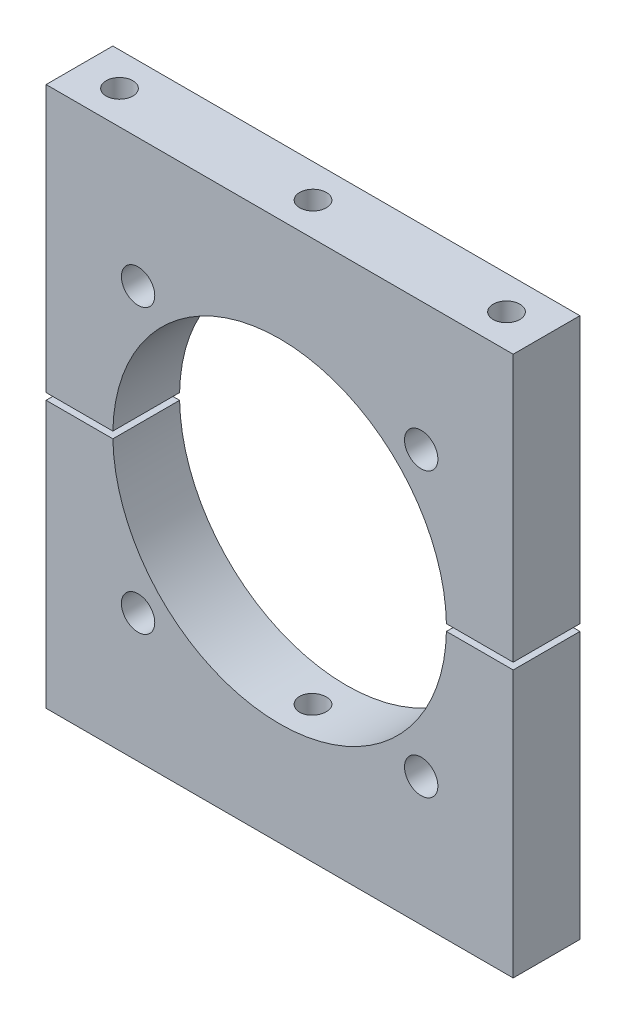
SolidWorks part; units mm, degrees
material "6061 Alloy"
ref_plane "Front Plane" through (0, 0, 0) normal (0, 0, 1) x (1, 0, 0)
ref_plane "Top Plane" through (0, 0, 0) normal (0, 1, 0) x (1, 0, 0)
ref_plane "Right Plane" through (0, 0, 0) normal (1, 0, 0) x (0, 0, -1)
sketch "Sketch1" plane through (0, 0, 0) normal (0, 0, 1) x (1, 0, 0)
  line L1 (0, 0) -> (70, 0)
  line L2 (0, 0) -> (0, 80.96)
  line L3 (0, 80.96) -> (70, 80.96)
  line L4 (70, 0) -> (70, 80.96)
  dimension "D1" = 80.96
  dimension "D2" = 70
extrude "Boss-Extrude1" add sketch "Sketch1" along normal blind 10
sketch "Sketch2" plane through (0, 0, 10) normal (0, 0, 1) x (1, 0, 0)
  line L0 (35, 80.96) -> (35, 0) construction
  line L1 (70, 80.96) -> (0, 80.96) construction
  line L2 (0, 0) -> (70, 0) construction
  line L3 (0, 40.48) -> (70, 40.48) construction
  line L4 (0, 80.96) -> (0, 0) construction
  line L5 (70, 0) -> (70, 80.96) construction
  line L6 (10.005, 40.98) -> (0, 40.98)
  line L7 (59.995, 40.98) -> (70, 40.98)
  line L8 (70, 40.98) -> (70, 39.98)
  line L9 (70, 39.98) -> (59.995, 39.98)
  line L10 (0, 39.98) -> (10.005, 39.98)
  line L11 (0, 39.98) -> (0, 40.98)
  arc A0 (10.005, 39.98) -> (59.995, 39.98) centre (35, 40.48) ccw
  arc A1 (59.995, 40.98) -> (10.005, 40.98) centre (35, 40.48) ccw
  point P22 (0, 40.48)
  dimension "D1" = 50
  dimension "D2" = 1
extrude "Cut-Extrude1" cut sketch "Sketch2" against normal blind 10
sketch "Sketch3" plane through (0, 80.96, 0) normal (0, 1, 0) x (1, 0, 0)
  line L0 (0, -5) -> (70, -5) construction
  line L1 (0, -10) -> (0, 0) construction
  line L2 (70, -10) -> (70, 0) construction
  circle A0 centre (6, -5) radius 2
  circle A1 centre (64, -5) radius 2
  circle A2 centre (35, -5) radius 2
  dimension "D1" = 4
  dimension "D2" = 4
  dimension "D4" = 6
  dimension "D5" = 4
  dimension "D3" = 6
extrude "Cut-Extrude2" cut sketch "Sketch3" against normal through all
sketch "Sketch6" plane through (0, 0, 10) normal (0, 0, 1) x (1, 0, 0)
  line L0 (0, 80.96) -> (70, 0) construction
  line L1 (35, 40.48) -> (13.7868, 61.6932) construction
  line L6 (0, 39.98) -> (10.005, 39.98) construction
  line L7 (0, 0) -> (70, 80.96) construction
  line L8 (35, 40.48) -> (13.7868, 61.6932) construction
  circle A0 centre (13.7868, 61.6932) radius 2.5
  circle A4 centre (13.7868, 19.2668) radius 2.5
  circle A6 centre (56.2132, 19.2668) radius 2.5
  circle A7 centre (56.2132, 61.6932) radius 2.5
  dimension "D3" = 5
  dimension "D2" = 45
  dimension "D5" = 30
  dimension "D4" = 4
extrude "Cut-Extrude3" cut sketch "Sketch6" against normal through all
